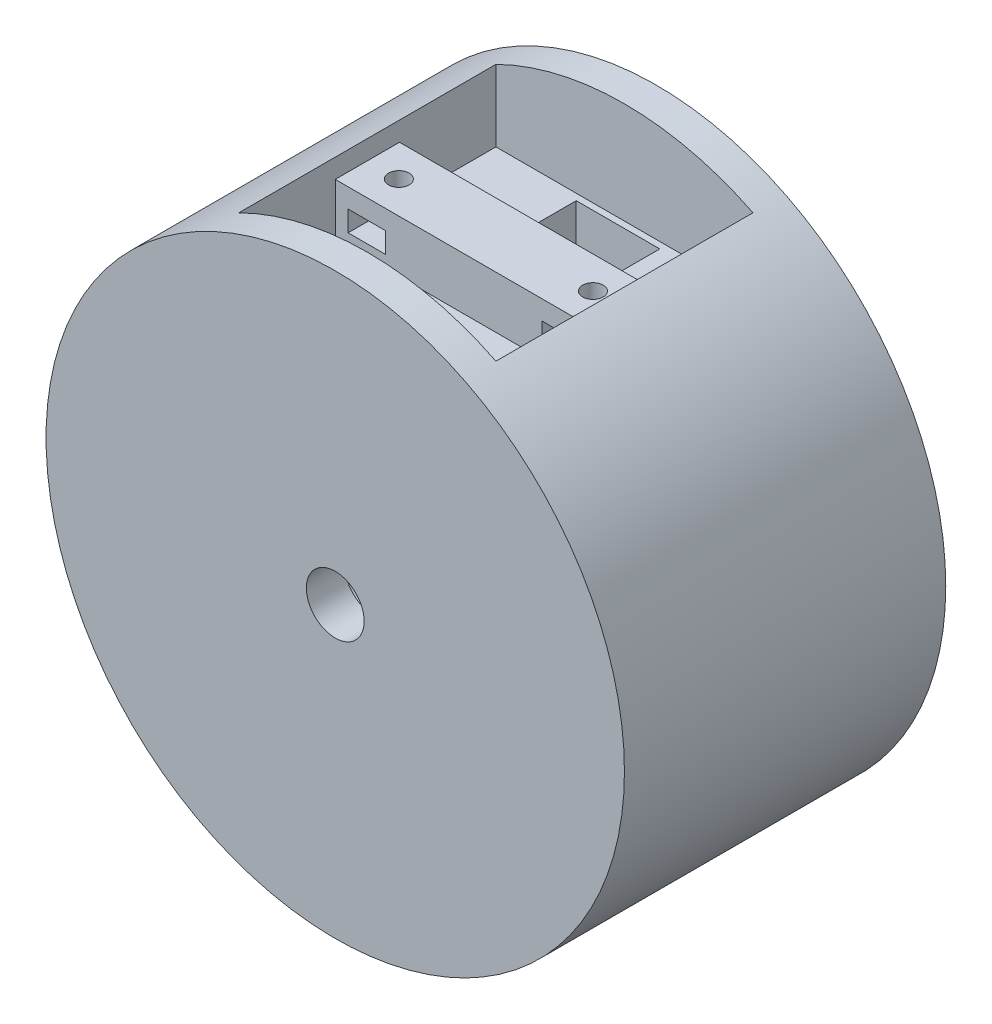
SolidWorks part; units mm, degrees
ref_plane "Plano frontal" through (0, 0, 0) normal (0, 0, 1) x (1, 0, 0)
ref_plane "Plano superior" through (0, 0, 0) normal (0, 1, 0) x (1, 0, 0)
ref_plane "Plano direito" through (0, 0, 0) normal (1, 0, 0) x (0, 0, -1)
sketch "Esboço1" plane through (0, 0, 0) normal (0, 0, 1) x (1, 0, 0)
  circle A0 centre (0, 0) radius 45
  dimension "D1" = 90
extrude "Ressalto-extrusão1" add sketch "Esboço1" along normal blind 50
sketch "Esboço2" plane through (0, 0, 50) normal (0, 0, 1) x (1, 0, 0)
  circle A0 centre (0, 0) radius 4.5
  dimension "D1" = 9
extrude "Corte-extrusão2" cut sketch "Esboço2" against normal blind 6
sketch "Esboço3" plane through (0, 0, 44) normal (0, 0, 1) x (1, 0, 0)
  line L0 (-6.5, -3.0735) -> (-6.5, 7.19)
  line L2 (-6.5, 7.19) -> (6.5, 7.19)
  line L3 (6.5, 7.19) -> (6.5, -3.0735)
  arc A1 (-6.5, -3.0735) -> (6.5, -3.0735) centre (0, 0) ccw
  dimension "D1" = 10.2635
  dimension "D4" = 7.19
  dimension "D2" = 13
  dimension "D3" = 13
extrude "Corte-extrusão3" cut sketch "Esboço3" against normal blind 7
sketch "Esboço4" plane through (0, 7.19, 0) normal (0, -1, 0) x (1, 0, 0)
  line L0 (45, 50) -> (-45, 50) construction
  line L1 (20, 30) -> (-20, 30)
  line L2 (20, 30) -> (20, 45)
  line L3 (20, 45) -> (-20, 45)
  line L4 (-20, 30) -> (-20, 45)
  line L5 (20, 30) -> (-20, 45) construction
  line L6 (20, 45) -> (-20, 30) construction
  line L7 (45, 0) -> (45, 50) construction
  point P0 (0, 37.5)
  dimension "D1" = 40
  dimension "D2" = 15
  dimension "D3" = 5
  dimension "D4" = 45
extrude "Corte-extrusão4" cut sketch "Esboço4" against normal blind 41
sketch "Esboço5" plane through (0, 0, 0) normal (0, 0, -1) x (-1, 0, 0)
  circle A0 centre (0, 0) radius 4.5
  dimension "D1" = 9
extrude "Corte-extrusão5" cut sketch "Esboço5" against normal blind 6
sketch "Esboço6" plane through (0, 0, 6) normal (0, 0, -1) x (-1, 0, 0)
  line L1 (-6.5, -3.0735) -> (-6.5, 7.19)
  line L2 (-6.5, 7.19) -> (6.5, 7.19)
  line L3 (6.5, 7.19) -> (6.5, -3.0735)
  arc A0 (-6.5, -3.0735) -> (6.5, -3.0735) centre (0, 0) ccw
  dimension "D1" = 14.38
  dimension "D2" = 13
  dimension "D3" = 10.2635
extrude "Corte-extrusão6" cut sketch "Esboço6" against normal blind 7
sketch "Esboço7" plane through (0, 7.19, 0) normal (0, -1, 0) x (1, 0, 0)
  line L0 (-45, 0) -> (45, 0) construction
  line L1 (-20, 20) -> (20, 20)
  line L2 (-20, 20) -> (-20, 5)
  line L3 (-20, 5) -> (20, 5)
  line L4 (20, 20) -> (20, 5)
  line L5 (-20, 20) -> (20, 5) construction
  line L6 (-20, 5) -> (20, 20) construction
  line L7 (-45, 50) -> (-45, 0) construction
  point P0 (0, 12.5)
  dimension "D1" = 5
  dimension "D2" = 40
  dimension "D3" = 15
  dimension "D4" = 45
extrude "Corte-extrusão7" cut sketch "Esboço7" against normal blind 47
sketch "Esboço8" plane through (0, 0, 30) normal (0, 0, 1) x (1, 0, 0)
  line L1 (-20, 40.3113) -> (-20, 47.3701)
  line L2 (-20, 47.3701) -> (20, 47.3701)
  line L3 (20, 47.3701) -> (20, 40.3113)
  line L4 (-20, 40.3113) -> (-20, 37.3113)
  line L5 (-20, 37.3113) -> (20, 37.3113)
  line L6 (20, 37.3113) -> (20, 40.3113)
  dimension "D1" = 7.0588
  dimension "D2" = 3
extrude "Corte-extrusão8" cut sketch "Esboço8" against normal up to next
sketch "Esboço9" plane through (0, 0, 20) normal (0, 0, -1) x (-1, 0, 0)
  line L1 (-12.2, 31.1113) -> (-18, 31.1113)
  line L2 (-12.2, 31.1113) -> (-12.2, 34.3113)
  line L3 (-12.2, 34.3113) -> (-18, 34.3113)
  line L4 (-18, 31.1113) -> (-18, 34.3113)
  line L5 (-12.2, 31.1113) -> (-18, 34.3113) construction
  line L6 (-12.2, 34.3113) -> (-18, 31.1113) construction
  line L7 (18, 31.1113) -> (12.2, 31.1113)
  line L8 (18, 31.1113) -> (18, 34.3113)
  line L9 (18, 34.3113) -> (12.2, 34.3113)
  line L10 (12.2, 31.1113) -> (12.2, 34.3113)
  line L11 (18, 31.1113) -> (12.2, 34.3113) construction
  line L12 (18, 34.3113) -> (12.2, 31.1113) construction
  line L13 (-20, 37.3113) -> (-20, 7.19) construction
  line L14 (20, 37.3113) -> (20, 7.19) construction
  line L16 (-20, 37.3113) -> (20, 37.3113) construction
  point P0 (-15.1, 32.7113)
  point P5 (15.1, 32.7113)
  dimension "D1" = 5.8
  dimension "D2" = 3.2
  dimension "D3" = 6.2
  dimension "D4" = 5.8
  dimension "D5" = 3.2
  dimension "D6" = 6.2
  dimension "D7" = 2
  dimension "D8" = 2
extrude "Corte-extrusão9" cut sketch "Esboço9" against normal up to next
sketch "Esboço11" plane through (0, 7.19, 0) normal (0, 1, 0) x (1, 0, 0)
  line L1 (-20, -5) -> (20, -5)
  line L2 (-20, -5) -> (-20, -20)
  line L3 (-20, -20) -> (20, -20)
  line L4 (20, -5) -> (20, -20)
  line L5 (20, -45) -> (-20, -45)
  line L6 (20, -45) -> (20, -30)
  line L7 (20, -30) -> (-20, -30)
  line L8 (-20, -45) -> (-20, -30)
  line L9 (-6.5, -44) -> (6.5, -44)
  line L10 (-6.5, -44) -> (-6.5, -37)
  line L11 (-6.5, -37) -> (6.5, -37)
  line L12 (6.5, -44) -> (6.5, -37)
  line L13 (-6.5, -13) -> (6.5, -13)
  line L14 (-6.5, -13) -> (-6.5, -6)
  line L15 (-6.5, -6) -> (6.5, -6)
  line L16 (6.5, -13) -> (6.5, -6)
extrude "Ressalto-extrusão2" add sketch "Esboço11" along normal blind 22
sketch "Esboço12" plane through (0, 37.3113, 0) normal (0, 1, 0) x (1, 0, 0)
  line L0 (-20, -45) -> (-20, -5) construction
  line L1 (-20, -30) -> (20, -30) construction
  line L2 (20, -5) -> (20, -45) construction
  circle A0 centre (-15.1, -25) radius 1.6
  circle A1 centre (15.1, -25) radius 1.6
  point P8 (-14.0418, -26.2372)
  dimension "D2" = 5
  dimension "D3" = 3.2
  dimension "D4" = 4.9
  dimension "D5" = 5
  dimension "D6" = 3.2
  dimension "D1" = 4.9
extrude "Corte-extrusão10" cut sketch "Esboço12" against normal blind 10
sketch "Esboço13" plane through (0, 0, 37) normal (0, 0, 1) x (1, 0, 0)
  circle A0 centre (0, 0) radius 4.5
  dimension "D1" = 9
extrude "Corte-extrusão11" cut sketch "Esboço13" against normal up to next
